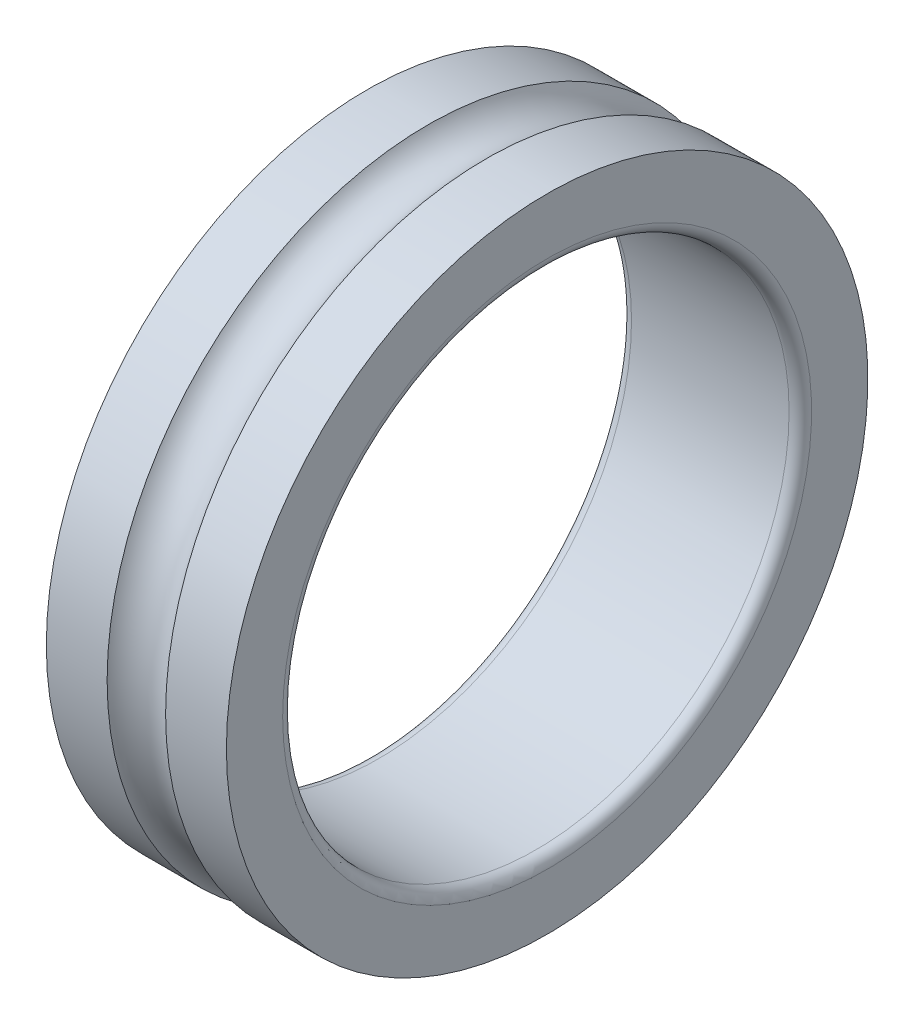
SolidWorks part; units mm, degrees
ref_plane "Front Plane" through (0, 0, 0) normal (0, 0, 1) x (1, 0, 0)
ref_plane "Top Plane" through (0, 0, 0) normal (0, 1, 0) x (1, 0, 0)
ref_plane "Right Plane" through (0, 0, 0) normal (1, 0, 0) x (0, 0, -1)
ref_plane "Plane1" through (0, 0, 0) normal (0, 0, 1) x (1, 0, 0)
sketch "Sketch1" plane through (0, 0, 0) normal (0, 0, 1) x (1, 0, 0)
  line L0 (1, 22.5) -> (15, 22.5)
  line L1 (16, 23.5) -> (16, 28.5)
  line L2 (16, 28.5) -> (10.5981, 28.5)
  line L3 (5.4019, 28.5) -> (0, 28.5)
  line L4 (0, 28.5) -> (0, 23.5)
  line L5 (16, 0) -> (0, 0) construction
  arc A0 (0, 23.5) -> (1, 22.5) centre (1, 23.5) ccw
  arc A1 (15, 22.5) -> (16, 23.5) centre (15, 23.5) ccw
  arc A2 (10.5981, 28.5) -> (5.4019, 28.5) centre (8, 30) cw
revolve "Revolve1" add sketch "Sketch1" angle 360 about L5
